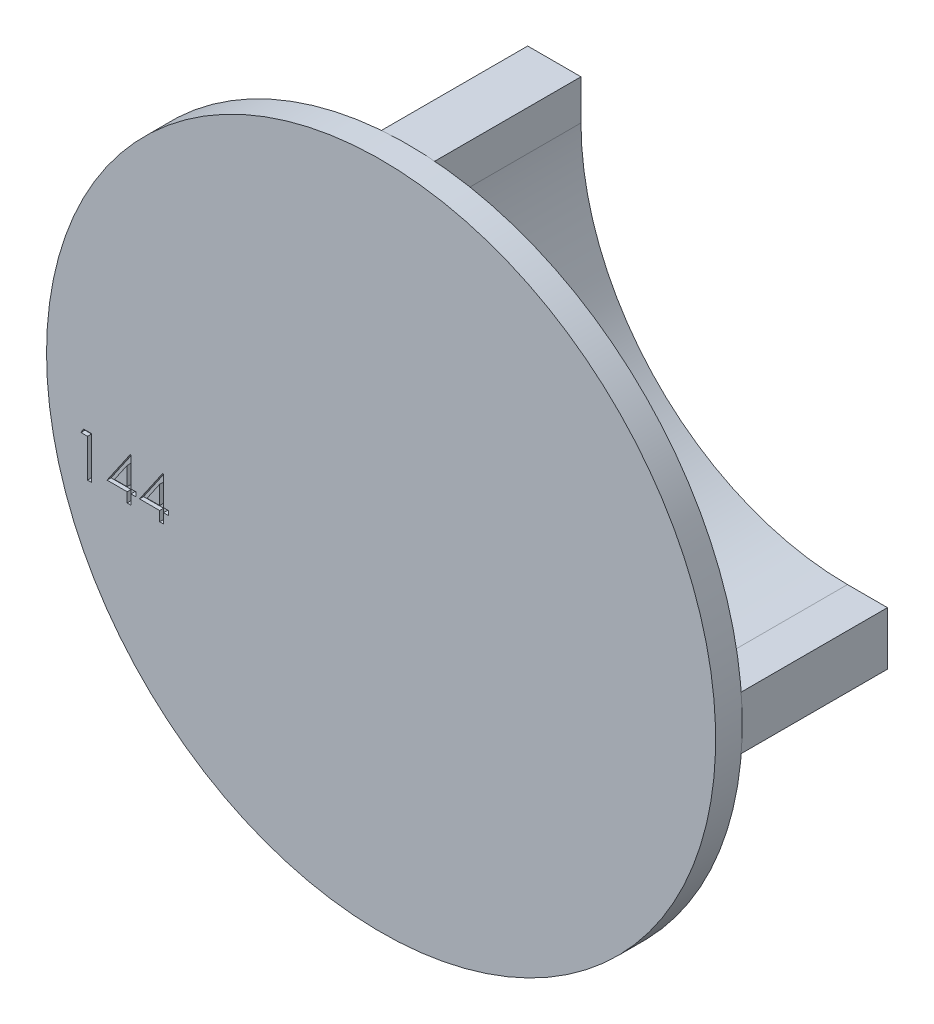
SolidWorks part; units mm, degrees
ref_plane "Front Plane" through (0, 0, 0) normal (0, 0, 1) x (1, 0, 0)
ref_plane "Top Plane" through (0, 0, 0) normal (0, 1, 0) x (1, 0, 0)
ref_plane "Right Plane" through (0, 0, 0) normal (1, 0, 0) x (0, 0, -1)
sketch "Sketch4" plane through (0, 0, 0) normal (0, 0, 1) x (1, 0, 0)
  line L1 (-25, 0) -> (25, 0)
  line L2 (-2, 25) -> (2, 25)
  line L3 (25, -2) -> (25, 2)
  line L4 (25, 2) -> (22, 2)
  line L5 (2, 22) -> (2, 25)
  line L6 (0, -13.75) -> (0, 13.75) construction
  line L7 (-25, 2) -> (-22, 2)
  line L8 (-25, -2) -> (-25, 2)
  line L9 (-2, 22) -> (-2, 25)
  line L10 (27.5, 0) -> (-27.5, 0) construction
  line L11 (25, -2) -> (22, -2)
  line L12 (2, -22) -> (2, -25)
  line L13 (-2, -25) -> (2, -25)
  line L14 (-2, -22) -> (-2, -25)
  line L15 (-25, -2) -> (-22, -2)
  arc A0 (22, 2) -> (2, 22) centre (22, 22) cw
  arc A1 (-22, 2) -> (-2, 22) centre (-22, 22) ccw
  arc A2 (22, -2) -> (2, -22) centre (22, -22) ccw
  arc A3 (-22, -2) -> (-2, -22) centre (-22, -22) cw
  dimension "D1" = 20
extrude "Boss-Extrude1" add sketch "Sketch4" along normal blind 13 from offset 2 contours A1 L7 L8 L1 L3 L4 A0 L5 L2 L9 | L15 A3 L14 L13 L12 A2 L11 L3 L1 L8
ref_plane "Plane1" through (0, 0, 15) normal (0, 0, -1) x (-1, 0, 0)
sketch "Sketch7" plane through (0, 0, 15) normal (0, 0, -1) x (-1, 0, 0)
  circle A0 centre (0, 0) radius 25.1067
extrude "Boss-Extrude3" add sketch "Sketch7" along normal blind 2
sketch "Sketch8" plane through (0, 0, 0) normal (0, 0, 1) x (1, 0, 0)
  circle A0 centre (0, 0) radius 5
extrude "Cut-Extrude2" cut sketch "Sketch8" along normal blind 4
sketch "Sketch11" plane through (0, 0, 15) normal (0, 0, 1) x (1, 0, 0)
  text T0 "144"
extrude "Cut-Extrude3" cut sketch "Sketch11" against normal blind 0.3
sketch "Sketch10" plane through (0, 0, 0) normal (0, 1, 0) x (1, 0, 0)
